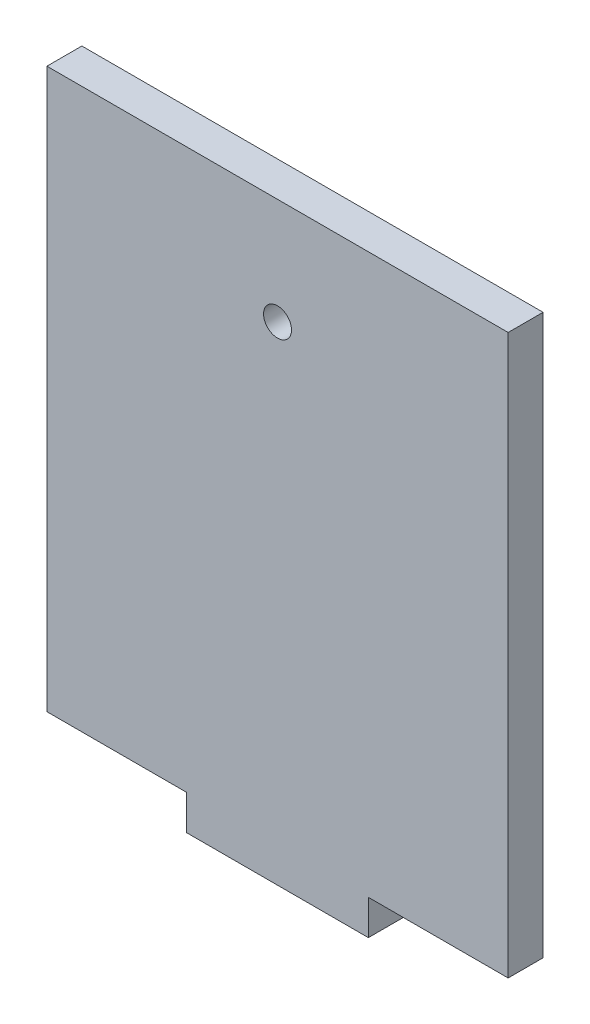
SolidWorks part; units mm, degrees
ref_plane "Front Plane" through (0, 0, 0) normal (0, 0, 1) x (1, 0, 0)
ref_plane "Top Plane" through (0, 0, 0) normal (0, 1, 0) x (1, 0, 0)
ref_plane "Right Plane" through (0, 0, 0) normal (1, 0, 0) x (0, 0, -1)
sketch "Sketch2" plane through (0, 0, 0) normal (0, 0, 1) x (1, 0, 0)
  line L0 (-16.51, 0) -> (0, 0)
  line L1 (0, 0) -> (0, 3.175)
  line L2 (0, 3.175) -> (12.7, 3.175)
  line L3 (12.7, 3.175) -> (12.7, 53.975)
  line L4 (12.7, 53.975) -> (-29.21, 53.975)
  line L5 (-16.51, 3.175) -> (-16.51, 0)
  line L6 (-29.21, 3.175) -> (-29.21, 53.975)
  line L7 (-16.51, 3.175) -> (-29.21, 3.175)
  dimension "D1" = 16.51
  dimension "D2" = 12.7
  dimension "D3" = 12.7
  dimension "D4" = 50.8
  dimension "D5" = 3.175
extrude "Boss-Extrude1" add sketch "Sketch2" along normal blind 3.175 contours L4 L6 L7 L5 L0 L1 L2 L3
sketch "Sketch3" plane through (0, 0, 3.175) normal (0, 0, 1) x (1, 0, 0)
  line L0 (12.7, 53.975) -> (-29.21, 53.975) construction
  circle A0 centre (-8.255, 44.323) radius 1.27
  dimension "D1" = 2.54
  dimension "D2" = 9.652
extrude "Cut-Extrude1" cut sketch "Sketch3" against normal through all
